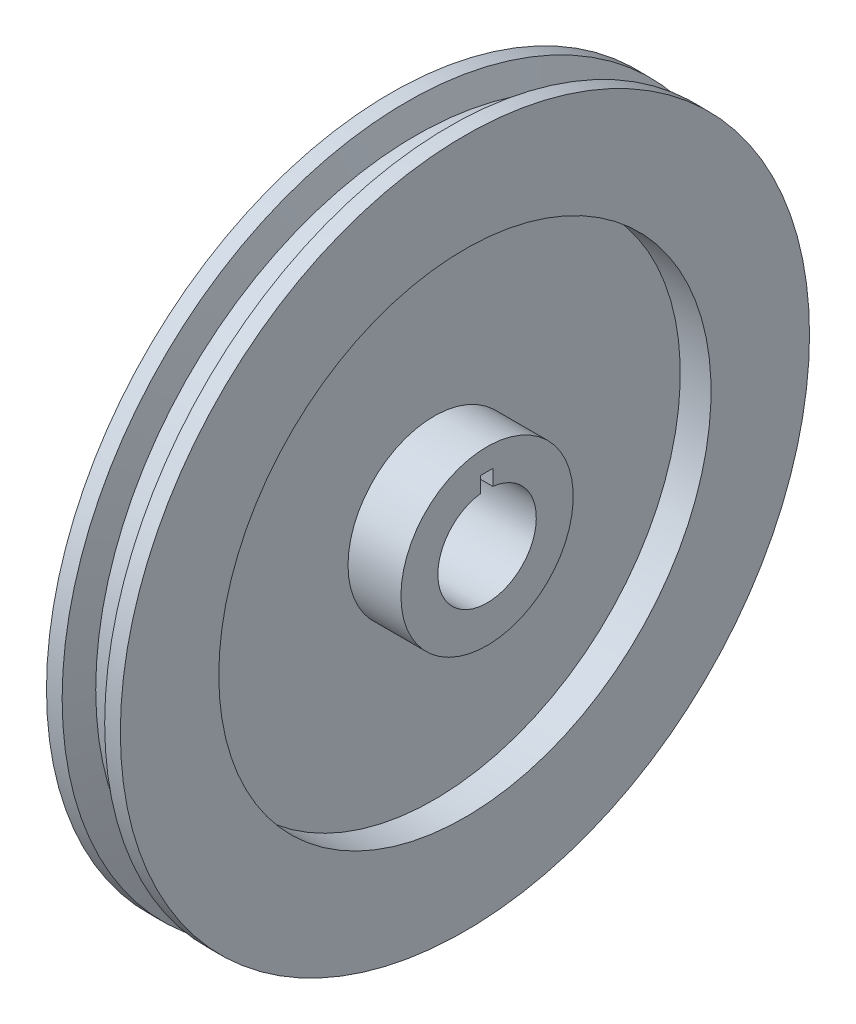
SolidWorks part; units mm, degrees
ref_plane "Front Plane" through (0, 0, 0) normal (0, 0, 1) x (1, 0, 0)
ref_plane "Top Plane" through (0, 0, 0) normal (0, 1, 0) x (1, 0, 0)
ref_plane "Right Plane" through (0, 0, 0) normal (1, 0, 0) x (0, 0, -1)
sketch "Sketch1" plane through (0, 0, 0) normal (0, 1, 0) x (1, 0, 0)
  line L0 (0, -223.6257) -> (0, -477.6257) construction
  line L1 (0, -477.6257) -> (219.4128, -477.6257) construction
  line L2 (-19.05, -33.1257) -> (254, -33.1257)
  line L3 (-254, -33.1257) -> (-82.55, -33.1257)
  line L4 (-254, -33.1257) -> (-254, -223.6257)
  line L5 (-254, -223.6257) -> (254, -223.6257)
  line L6 (254, -33.1257) -> (254, -223.6257)
  line L7 (-160.5242, 1300.3743) -> (-114.3, 1173.3743)
  line L8 (-114.3, 1173.3743) -> (12.7, 1173.3743)
  line L10 (-82.55, 792.3743) -> (-82.55, -33.1257)
  line L12 (-19.05, 792.3743) -> (-19.05, -33.1257)
  line L13 (12.7, 1173.3743) -> (58.9242, 1300.3743)
  line L14 (58.9242, 1300.3743) -> (139.7, 1300.3743)
  line L15 (-19.05, 792.3743) -> (139.7, 792.3743)
  line L16 (-241.3, 1300.3743) -> (-160.5242, 1300.3743)
  line L17 (-241.3, 1300.3743) -> (-241.3, 792.3743)
  line L18 (-241.3, 792.3743) -> (-82.55, 792.3743)
  line L19 (139.7, 1300.3743) -> (139.7, 792.3743)
  point P3 (0, -208.6043)
  point P9 (0, 161.0468)
  point P14 (0, 599.9403)
  dimension "D1" = 508
  dimension "D2" = 63.5
  dimension "D3" = 254
  dimension "D4" = 444.5
  dimension "D5" = 1270
  dimension "D6" = 1778
  dimension "D7" = 381
  dimension "D8" = 40
  dimension "D9" = 127
  dimension "D10" = 127
revolve "Revolve1" add sketch "Sketch1" angle 360 about L1
sketch "Sketch2" plane through (-254, 0, 0) normal (-1, 0, 0) x (0, 0, 1)
  line L1 (448.3181, 332.1985) -> (511.8181, 332.1985)
  line L2 (448.3181, 332.1985) -> (448.3181, 179.7985)
  line L3 (448.3181, 179.7985) -> (511.8181, 179.7985)
  line L4 (511.8181, 332.1985) -> (511.8181, 179.7985)
  line L5 (448.3181, 332.1985) -> (511.8181, 179.7985) construction
  line L6 (448.3181, 179.7985) -> (511.8181, 332.1985) construction
  point P0 (480.0681, 255.9985)
  dimension "D1" = 63.5
  dimension "D2" = 152.4
extrude "Cut-Extrude1" cut sketch "Sketch2" against normal blind 1270
